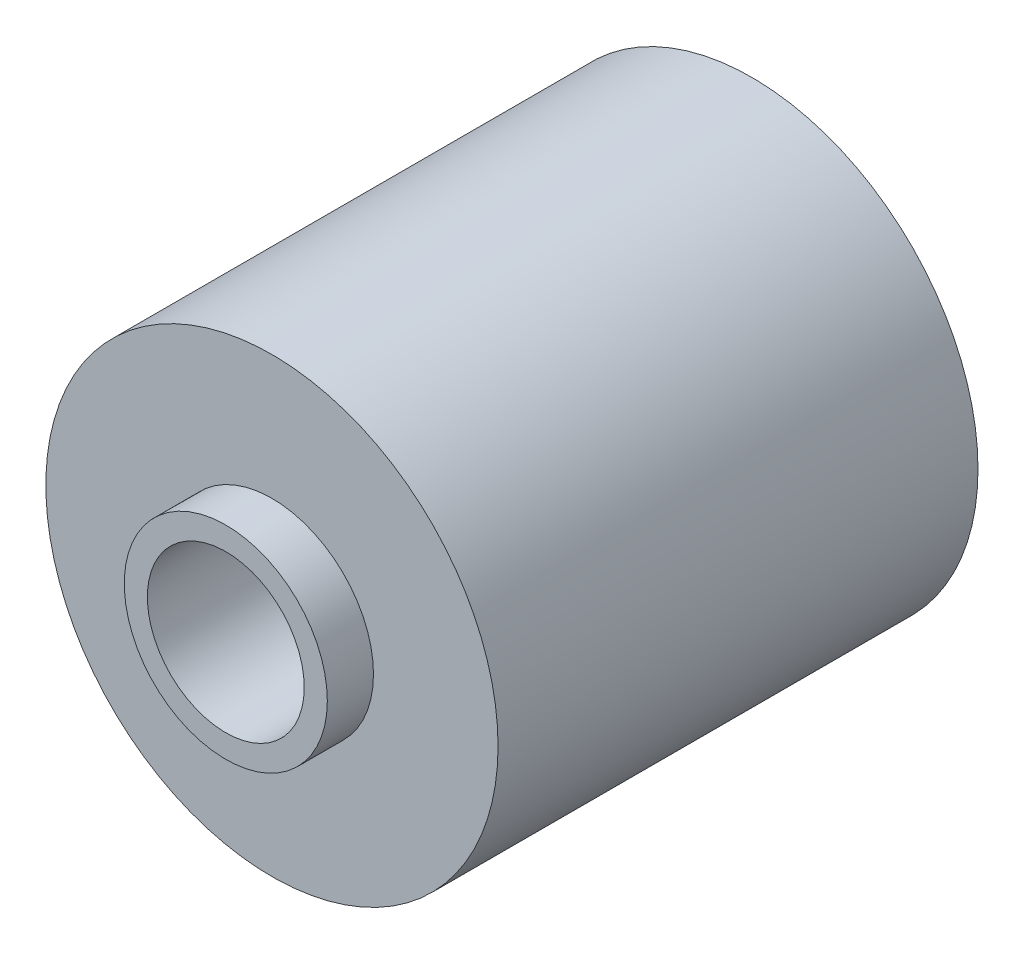
SolidWorks part; units mm, degrees
ref_plane "Front Plane" through (0, 0, 0) normal (0, 0, 1) x (1, 0, 0)
ref_plane "Top Plane" through (0, 0, 0) normal (0, 1, 0) x (1, 0, 0)
ref_plane "Right Plane" through (0, 0, 0) normal (1, 0, 0) x (0, 0, -1)
sketch "Sketch1" plane through (0, 0, 0) normal (0, 0, 1) x (1, 0, 0)
  circle A0 centre (0, 0) radius 1.7
  circle A2 centre (0, 0) radius 4.9
  dimension "D1" = 3.4
  dimension "D2" = 9.8
extrude "Boss-Extrude1" add sketch "Sketch1" along normal blind 10.4
sketch "Sketch2" plane through (0, 0, 10.4) normal (0, 0, 1) x (1, 0, 0)
  circle A0 centre (0, 0) radius 1.7
  circle A2 centre (0, 0) radius 2.2
  dimension "D1" = 3.4
  dimension "D2" = 0.5
extrude "Boss-Extrude2" add sketch "Sketch2" along normal blind 1
sketch "Sketch3" plane through (0, 0, 0) normal (0, 0, 1) x (1, 0, 0)
  circle A0 centre (0, 0) radius 2.2
  circle A1 centre (0, 0) radius 1.7
  dimension "D1" = 4.4
  dimension "D2" = 3.4
extrude "Boss-Extrude3" add sketch "Sketch3" against normal blind 1
